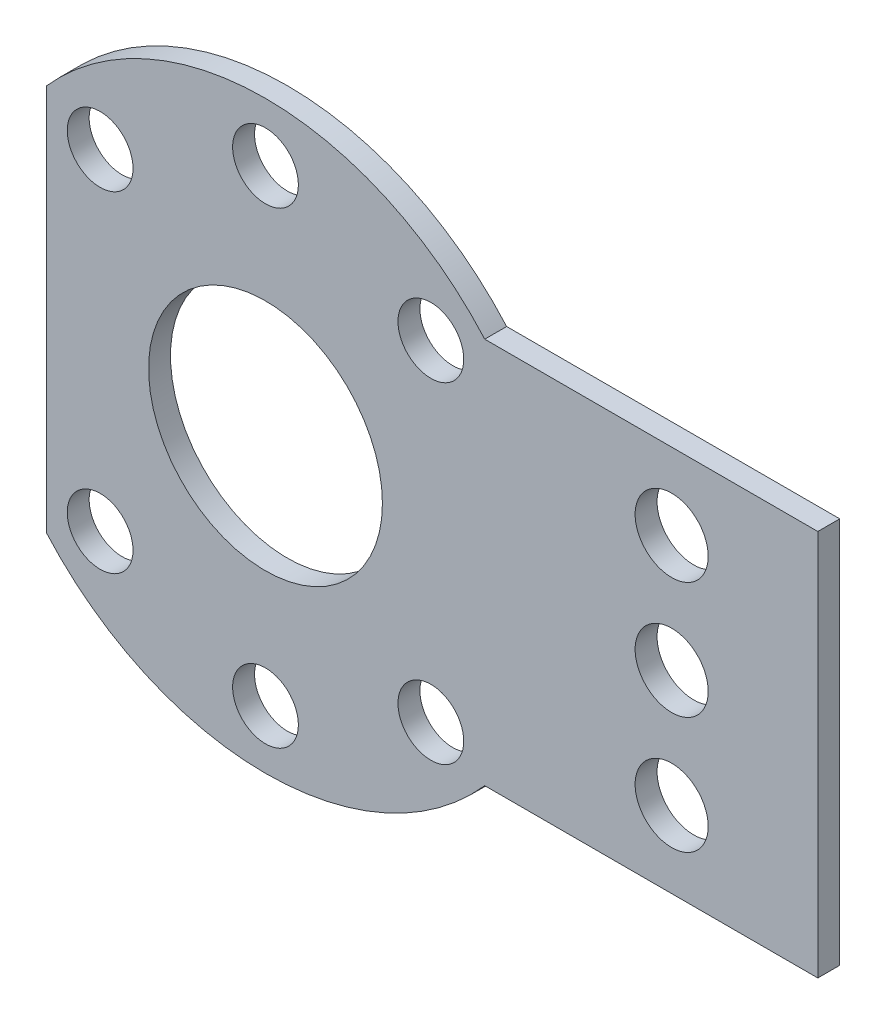
SolidWorks part; units mm, degrees
material "Galvanized Steel"
ref_plane "Front Plane" through (0, 0, 0) normal (0, 0, 1) x (1, 0, 0)
ref_plane "Top Plane" through (0, 0, 0) normal (0, 1, 0) x (1, 0, 0)
ref_plane "Right Plane" through (0, 0, 0) normal (1, 0, 0) x (0, 0, -1)
sketch "Sketch1" plane through (0, 0, 0) normal (0, 0, 1) x (1, 0, 0)
  line L2 (15, 13.2288) -> (17.79, 13.2288)
  line L3 (17.79, 13.2288) -> (17.79, -13.2288) construction
  line L4 (-15, 13.2288) -> (-15, -13.2288)
  line L5 (15, -13.2288) -> (15, 13.2288)
  line L6 (-15, 13.2288) -> (-15, -13.2288)
  line L7 (15, -13.2288) -> (15, 13.2288) construction
  line L8 (17.79, -13.2288) -> (15, -13.2288)
  line L9 (17.79, 13.2288) -> (37.79, 13.2288)
  line L10 (37.79, 13.2288) -> (37.79, -13.2288)
  line L11 (37.79, -13.2288) -> (17.79, -13.2288)
  line L12 (27.79, 13.2288) -> (27.79, -13.2288) construction
  arc A4 (15, 13.2288) -> (-15, 13.2288) centre (0, 0) ccw
  arc A5 (-15, -13.2288) -> (15, -13.2288) centre (0, 0) ccw
  arc A6 (15, 13.2288) -> (-15, 13.2288) centre (0, 0) ccw
  arc A7 (-15, -13.2288) -> (15, -13.2288) centre (0, 0) ccw
  circle A8 centre (-11.3137, 11.3137) radius 2.25
  circle A9 centre (-11.3137, 11.3137) radius 2.25
  circle A11 centre (0, 16) radius 2.25
  circle A12 centre (0, 16) radius 2.25
  circle A14 centre (11.3137, 11.3137) radius 2.25
  circle A15 centre (11.3137, 11.3137) radius 2.25
  circle A17 centre (-11.3137, -11.3137) radius 2.25
  circle A18 centre (-11.3137, -11.3137) radius 2.25
  circle A20 centre (0, -16) radius 2.25
  circle A21 centre (0, -16) radius 2.25
  circle A22 centre (0, 0) radius 8
  circle A23 centre (11.3137, -11.3137) radius 2.25
  circle A24 centre (11.3137, -11.3137) radius 2.25
  circle A31 centre (27.79, 0) radius 2.5
  circle A32 centre (27.79, 8) radius 2.5
  circle A33 centre (27.79, -8) radius 2.5
  dimension "D8" = 16
  dimension "D11" = 5
  dimension "D9" = 2.79
  dimension "D10" = 20
  dimension "D12" = 8
  dimension "D13" = 8
  dimension "D1" = 0
  dimension "D2" = 0
  dimension "D3" = 0
  dimension "D4" = 0
  dimension "D5" = 0
  dimension "D6" = 0
  dimension "D7" = 0
extrude "Boss-Extrude1" add sketch "Sketch1" along normal blind 1.5
